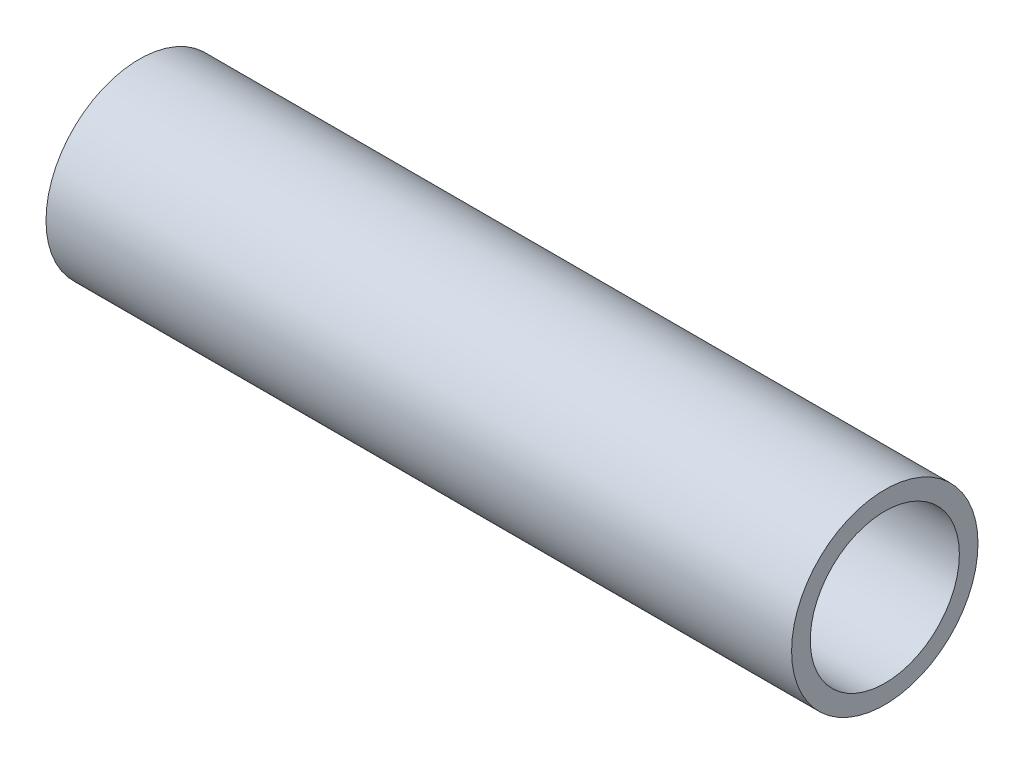
SolidWorks part; units mm, degrees
ref_plane "Front" through (0, 0, 0) normal (0, 0, 1) x (1, 0, 0)
ref_plane "Top" through (0, 0, 0) normal (0, 1, 0) x (1, 0, 0)
ref_plane "Right" through (0, 0, 0) normal (1, 0, 0) x (0, 0, -1)
sketch "Skizze1" plane through (0, 0, 0) normal (1, 0, 0) x (0, 0, -1)
  circle A0 centre (0, 0) radius 1
  circle A1 centre (0, 0) radius 1.25
  dimension "D1" = 2.5
  dimension "D2" = 2
extrude "Aufsatz-Linear austragen1" add sketch "Skizze1" along normal mid plane 10
